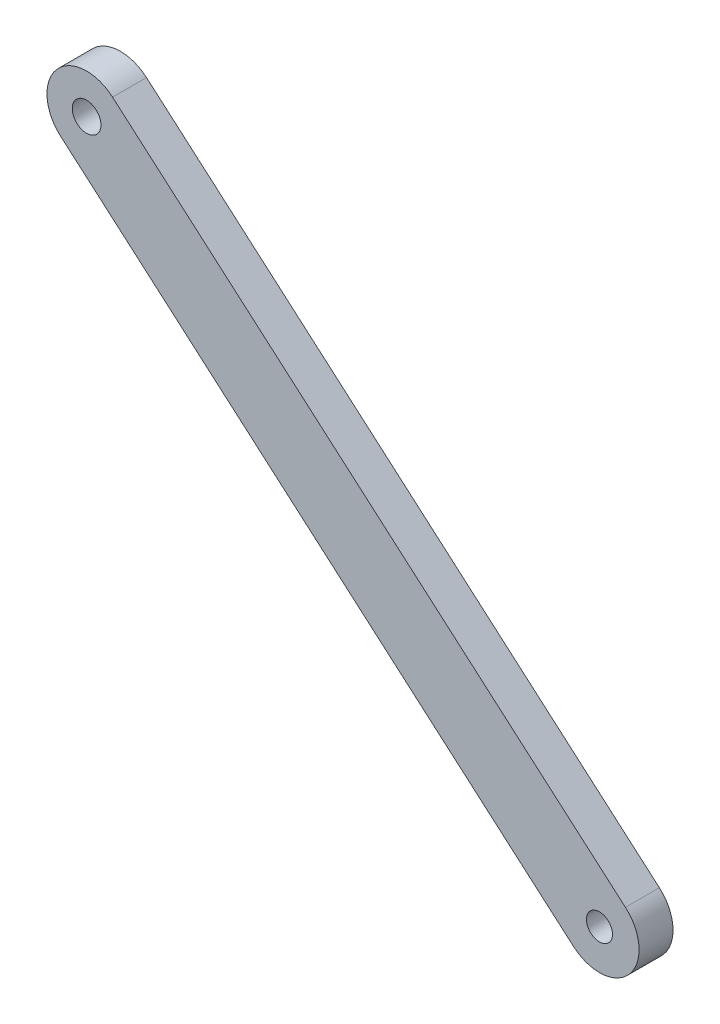
SolidWorks part; units mm, degrees
ref_plane "Plan de face" through (0, 0, 0) normal (0, 0, 1) x (1, 0, 0)
ref_plane "Plan de dessus" through (0, 0, 0) normal (0, 1, 0) x (1, 0, 0)
ref_plane "Plan de droite" through (0, 0, 0) normal (1, 0, 0) x (0, 0, -1)
sketch "Esquisse1" plane through (0, 0, 0) normal (0, 0, 1) x (1, 0, 0)
  line L0 (19.3041, -22.1274) -> (-26.0063, 17.204) construction
  line L1 (17.0098, -24.7705) -> (-28.3006, 14.5609)
  line L2 (21.5985, -19.4843) -> (-23.7119, 19.8472)
  arc A0 (17.0098, -24.7705) -> (21.5985, -19.4843) centre (19.3041, -22.1274) ccw
  arc A1 (-23.7119, 19.8472) -> (-28.3006, 14.5609) centre (-26.0063, 17.204) ccw
  circle A2 centre (19.3041, -22.1274) radius 1.15
  circle A3 centre (-26.0063, 17.204) radius 1.2681
  point P2 (-3.3511, -2.4617)
  dimension "D1" = 7
  dimension "D2" = 60
extrude "Boss.-Extru.1" add sketch "Esquisse1" along normal blind 3
